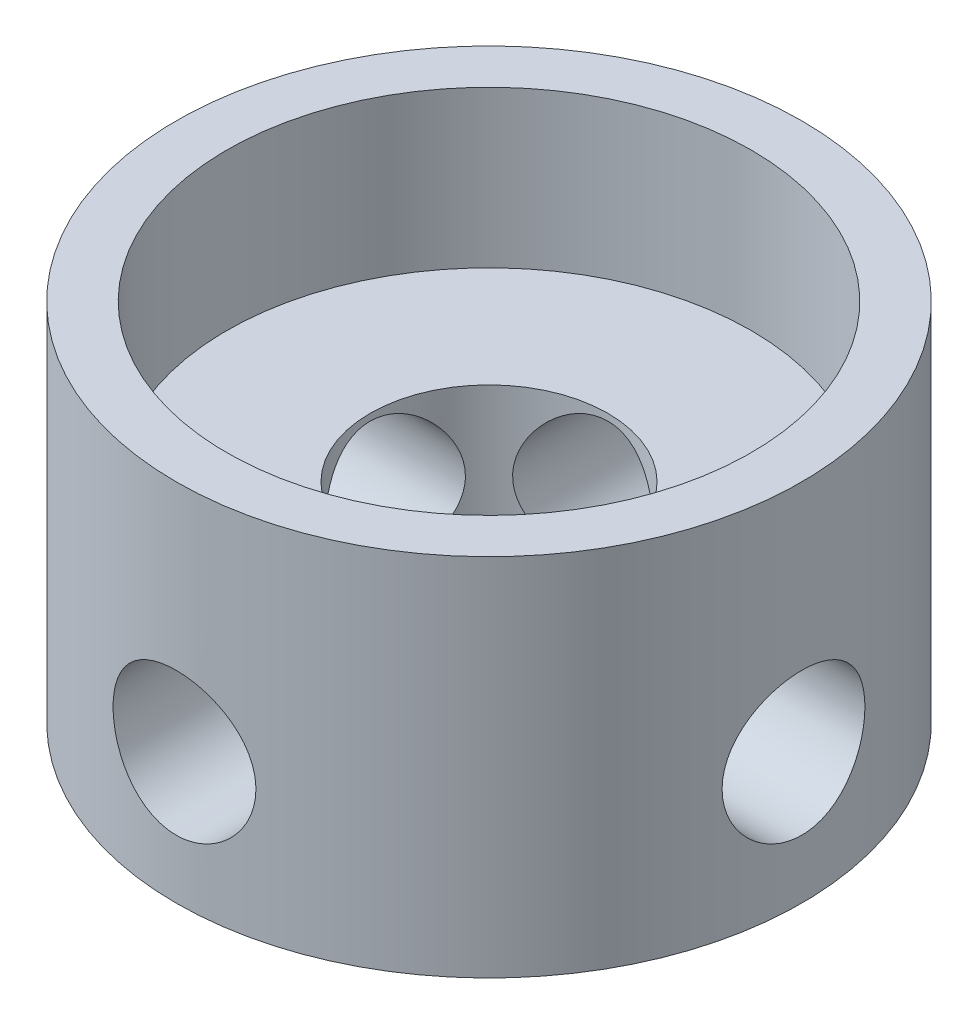
SolidWorks part; units mm, degrees
ref_plane "Front Plane" through (0, 0, 0) normal (0, 0, 1) x (1, 0, 0)
ref_plane "Top Plane" through (0, 0, 0) normal (0, 1, 0) x (1, 0, 0)
ref_plane "Right Plane" through (0, 0, 0) normal (1, 0, 0) x (0, 0, -1)
sketch "Sketch1" plane through (0, 0, 0) normal (0, 1, 0) x (1, 0, 0)
  circle A0 centre (0, 0) radius 2.8956
  circle A1 centre (0, 0) radius 7.62
  dimension "D1" = 5.7912
  dimension "D2" = 15.24
extrude "Boss-Extrude1" add sketch "Sketch1" along normal blind 5.08
sketch "Sketch2" plane through (0, 5.08, 0) normal (0, 1, 0) x (1, 0, 0)
  circle A0 centre (0, 0) radius 6.3881
  circle A1 centre (0, 0) radius 7.62
  dimension "D1" = 12.7762
  dimension "D2" = 15.24
extrude "Boss-Extrude2" add sketch "Sketch2" along normal blind 3.81
sketch "Sketch3" plane through (0, 0, 0) normal (0, 0, 1) x (1, 0, 0)
  line L0 (-7.62, 0) -> (7.62, 0) construction
  circle A0 centre (0, 3.175) radius 1.7399
  dimension "D2" = 3.4798
  dimension "D1" = 3.175
extrude "Cut-Extrude1" cut sketch "Sketch3" against normal mid plane 25.4
sketch "Sketch4" plane through (0, 0, 0) normal (1, 0, 0) x (0, 0, -1)
  line L0 (-7.62, 0) -> (7.62, 0) construction
  circle A0 centre (0, 3.175) radius 1.7399
  dimension "D2" = 3.4798
  dimension "D1" = 3.175
extrude "Cut-Extrude2" cut sketch "Sketch4" against normal mid plane 25.4
